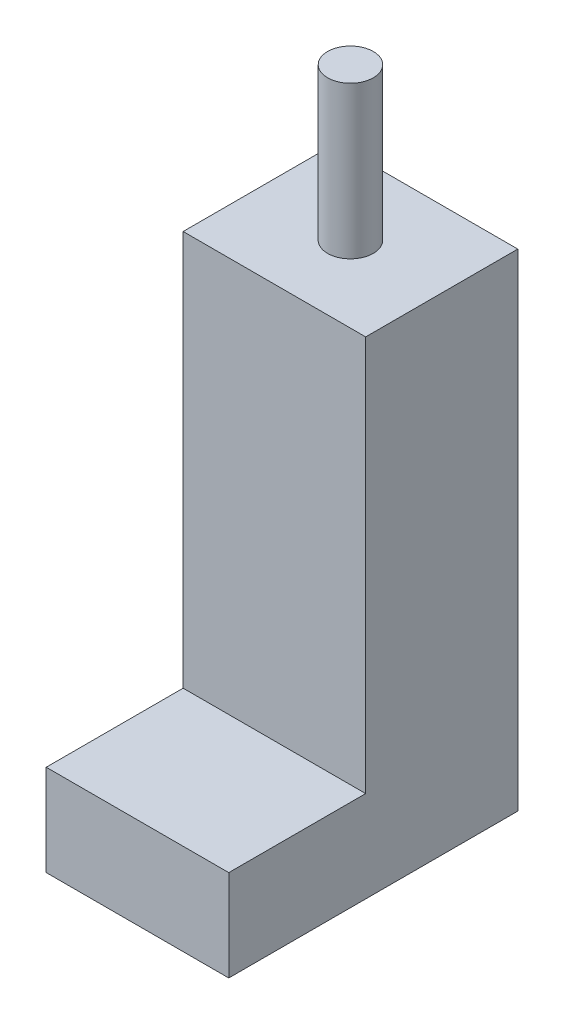
SolidWorks part; units mm, degrees
ref_plane "前视基准面" through (0, 0, 0) normal (0, 0, 1) x (1, 0, 0)
ref_plane "上视基准面" through (0, 0, 0) normal (0, 1, 0) x (1, 0, 0)
ref_plane "右视基准面" through (0, 0, 0) normal (1, 0, 0) x (0, 0, -1)
sketch "草图1" plane through (0, 0, 0) normal (0, 1, 0) x (1, 0, 0)
  line L1 (-6, 5) -> (6, 5)
  line L2 (-6, 5) -> (-6, -5)
  line L3 (-6, -5) -> (6, -5)
  line L4 (6, 5) -> (6, -5)
  line L5 (-6, 5) -> (6, -5) construction
  line L6 (-6, -5) -> (6, 5) construction
  point P0 (0, 0)
  dimension "D1" = 12
  dimension "D2" = 10
extrude "凸台-拉伸1" add sketch "草图1" along normal blind 32 contours L2 L3 L4 L1
sketch "草图2" plane through (0, 32, 0) normal (0, 1, 0) x (1, 0, 0)
  circle A0 centre (0, 0) radius 1.5
  dimension "D1" = 3
extrude "凸台-拉伸2" add sketch "草图2" along normal blind 10
sketch "草图3" plane through (0, 0, 5) normal (0, 0, 1) x (1, 0, 0)
  line L0 (6, 32) -> (6, 0) construction
  line L1 (-6, 0) -> (6, 0)
  line L2 (-6, 0) -> (-6, 6)
  line L3 (-6, 6) -> (6, 6)
  line L4 (6, 0) -> (6, 6)
  dimension "D1" = 6
extrude "凸台-拉伸3" add sketch "草图3" along normal blind 9
